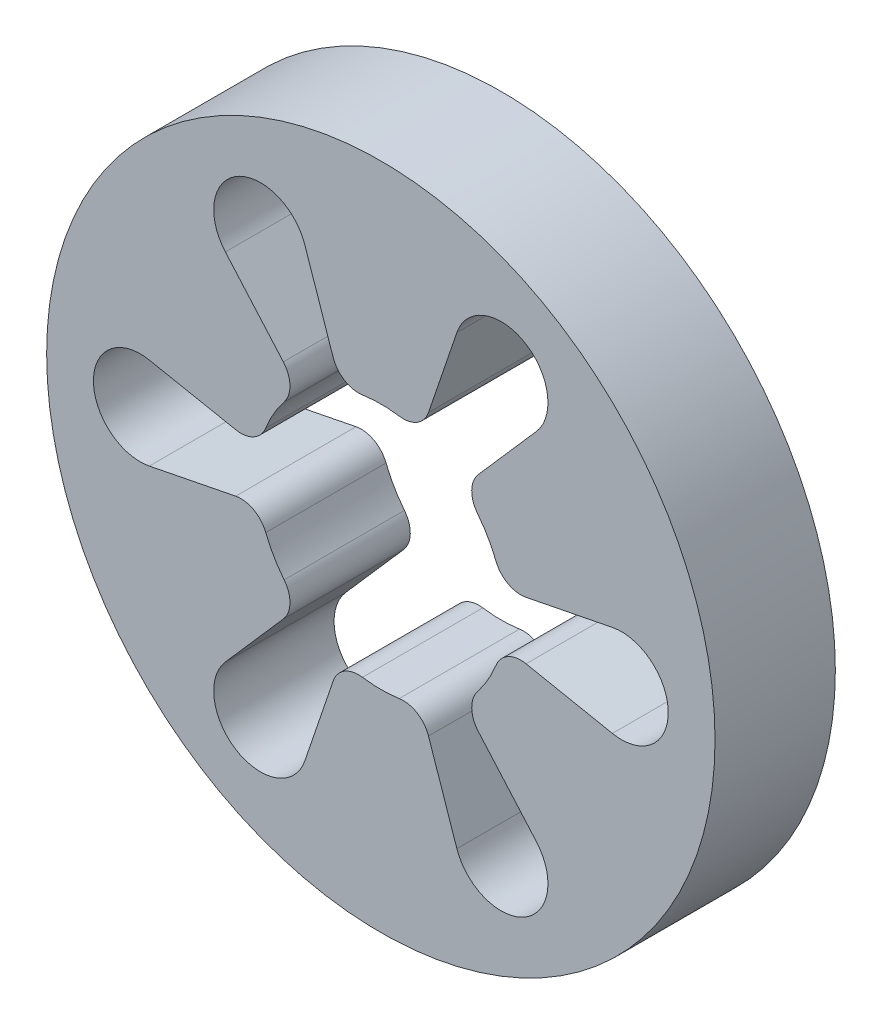
SolidWorks part; units mm, degrees
ref_plane "Front Plane" through (0, 0, 0) normal (1, 0, 0) x (0, 1, 0)
ref_plane "Top Plane" through (0, 0, 0) normal (0, 0, 1) x (0, 1, 0)
ref_plane "Right Plane" through (0, 0, 0) normal (0, 1, 0) x (-1, 0, 0)
sketch "Sketch1" plane through (0, 0, 0) normal (0, 0, 1) x (0, 1, 0)
  line L0 (0, 158.75) -> (0, 0) construction
  line L4 (21.8008, 109.9785) -> (13.6694, 68.9578)
  line L5 (52.8845, 46.3169) -> (84.3437, 73.8693)
  line L6 (0, 114.3) -> (98.9867, 57.15) construction
  line L7 (49.4934, 85.725) -> (0, 0) construction
  line L8 (106.1446, 36.1092) -> (66.5539, 22.6409)
  line L9 (66.5539, -22.6409) -> (106.1446, -36.1092)
  line L10 (84.3437, -73.8693) -> (52.8845, -46.3169)
  line L11 (13.6694, -68.9578) -> (21.8008, -109.9785)
  line L12 (-21.8008, -109.9785) -> (-13.6694, -68.9578)
  line L13 (-52.8845, -46.3169) -> (-84.3437, -73.8693)
  line L14 (-106.1446, -36.1092) -> (-66.5539, -22.6409)
  line L15 (-66.5539, 22.6409) -> (-106.1446, 36.1092)
  line L16 (-84.3437, 73.8693) -> (-52.8845, 46.3169)
  line L17 (-13.6694, 68.9578) -> (-21.8008, 109.9785)
  circle A0 centre (0, 0) radius 95.25 construction
  circle A1 centre (0, 0) radius 158.75
  circle A3 centre (0, 0) radius 114.3 construction
  circle A10 centre (0, 0) radius 58.7375 construction
  arc A11 (21.4822, 54.6682) -> (36.603, 45.9382) centre (0, 0) cw
  arc A12 (36.603, 45.9382) -> (52.8845, 46.3169) centre (44.5171, 55.8708) ccw
  arc A13 (13.6694, 68.9578) -> (21.4822, 54.6682) centre (26.127, 66.4883) ccw
  arc A16 (66.5539, 22.6409) -> (58.0851, 8.73) centre (70.6441, 10.6176) ccw
  arc A17 (58.0851, 8.73) -> (58.0851, -8.73) centre (0, 0) cw
  arc A18 (58.0851, -8.73) -> (66.5539, -22.6409) centre (70.6441, -10.6176) ccw
  arc A21 (52.8845, -46.3169) -> (36.603, -45.9382) centre (44.5171, -55.8708) ccw
  arc A22 (36.603, -45.9382) -> (21.4822, -54.6682) centre (0, 0) cw
  arc A23 (21.4822, -54.6682) -> (13.6694, -68.9578) centre (26.127, -66.4883) ccw
  arc A26 (-13.6694, -68.9578) -> (-21.4822, -54.6682) centre (-26.127, -66.4883) ccw
  arc A27 (-21.4822, -54.6682) -> (-36.603, -45.9382) centre (0, 0) cw
  arc A28 (-36.603, -45.9382) -> (-52.8845, -46.3169) centre (-44.5171, -55.8708) ccw
  arc A31 (-66.5539, -22.6409) -> (-58.0851, -8.73) centre (-70.6441, -10.6176) ccw
  arc A32 (-58.0851, -8.73) -> (-58.0851, 8.73) centre (0, 0) cw
  arc A33 (-58.0851, 8.73) -> (-66.5539, 22.6409) centre (-70.6441, 10.6176) ccw
  arc A36 (-52.8845, 46.3169) -> (-36.603, 45.9382) centre (-44.5171, 55.8708) ccw
  arc A37 (-36.603, 45.9382) -> (-21.4822, 54.6682) centre (0, 0) cw
  arc A38 (-21.4822, 54.6682) -> (-13.6694, 68.9578) centre (-26.127, 66.4883) ccw
  arc A46 (21.8008, 109.9785) -> (-21.8008, 109.9785) centre (0, 114.3) ccw
  arc A52 (106.1446, 36.1092) -> (84.3437, 73.8693) centre (98.9867, 57.15) ccw
  arc A53 (84.3437, -73.8693) -> (106.1446, -36.1092) centre (98.9867, -57.15) ccw
  arc A54 (-21.8008, -109.9785) -> (21.8008, -109.9785) centre (0, -114.3) ccw
  arc A55 (-106.1446, -36.1092) -> (-84.3437, -73.8693) centre (-98.9867, -57.15) ccw
  arc A56 (-84.3437, 73.8693) -> (-106.1446, 36.1092) centre (-98.9867, 57.15) ccw
  point P19 (0, 0)
  point P26 (44.1867, 38.6992)
  point P29 (11.4212, 57.6164)
  point P40 (0, 0)
  point P98 (0, 0)
  dimension "D1" = 190.5
  dimension "D2" = 317.5
  dimension "D4" = 22.225
  dimension "D5" = 228.6
  dimension "D7" = 117.475
  dimension "D9" = 12.7
  dimension "D11" = 6
  dimension "D3" = 6
extrude "Boss-Extrude1" add sketch "Sketch1" along normal mid plane 57.15
sketch "Sketch2" [suppressed] plane through (0, 0, 28.575) normal (0, 0, 1) x (1, 0, 0)
  line L0 (0, 0) -> (79.375, 137.4815)
  line L1 (0, 0) -> (-79.375, 137.4815)
  circle A0 centre (0, 0) radius 158.75 construction
  arc A1 (73.8693, 84.3437) -> (36.1092, 106.1446) centre (57.15, 98.9867) ccw construction
  arc A2 (-36.1092, 106.1446) -> (-73.8693, 84.3437) centre (-57.15, 98.9867) ccw construction
  point P9 (68.2625, 118.2341)
  point P13 (-68.2625, 118.2341)
split "Split1" [suppressed] bodies to split 101
